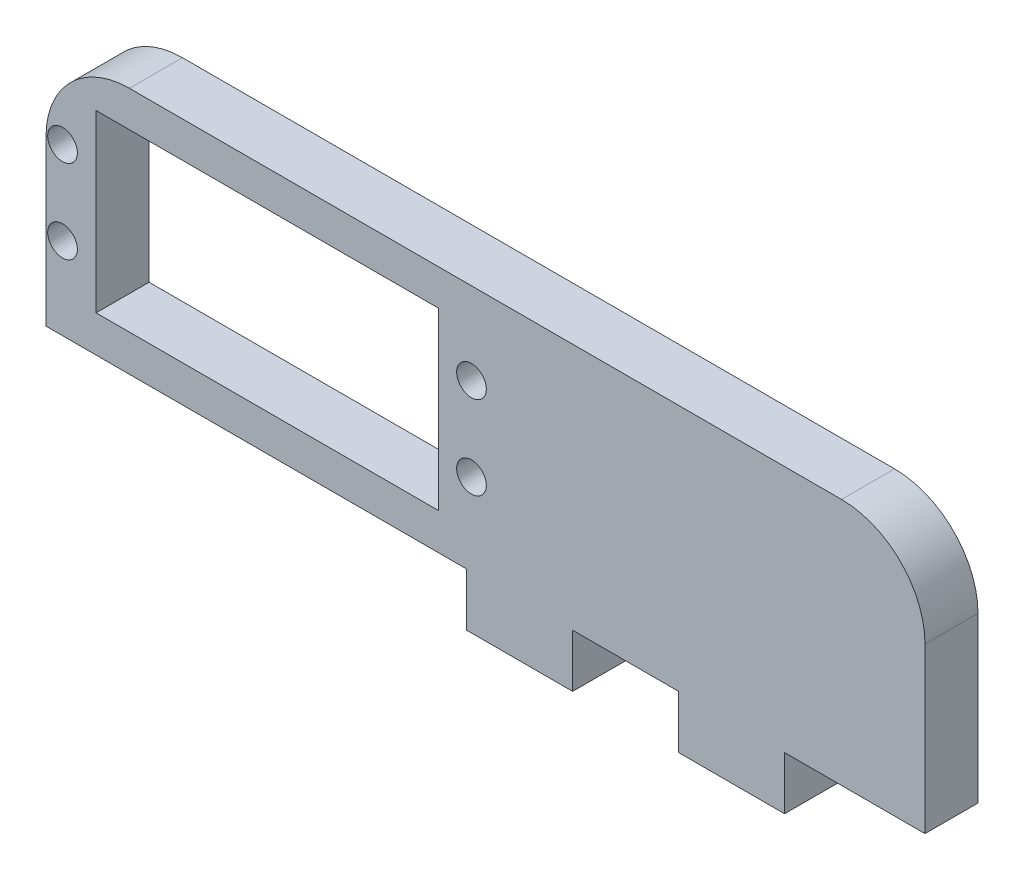
SolidWorks part; units mm, degrees
ref_plane "Front Plane" through (0, 0, 0) normal (0, 0, 1) x (1, 0, 0)
ref_plane "Top Plane" through (0, 0, 0) normal (0, 1, 0) x (1, 0, 0)
ref_plane "Right Plane" through (0, 0, 0) normal (1, 0, 0) x (0, 0, -1)
sketch "Sketch1" plane through (0, 0, 0) normal (0, 0, 1) x (1, 0, 0)
  line L0 (19.05, 38.1) -> (19.05, 44.45)
  line L1 (19.05, 44.45) -> (35.8724, 44.45)
  line L2 (38.1, 44.45) -> (-38.1, 44.45) construction
  line L3 (35.8724, 44.45) -> (35.8724, 74.1299)
  line L4 (35.8724, 74.1299) -> (-49.45, 74.1299)
  line L5 (19.05, 38.1) -> (6.35, 38.1)
  line L6 (6.35, 38.1) -> (6.35, 44.45)
  line L7 (6.35, 44.45) -> (-6.35, 44.45)
  line L8 (-6.35, 44.45) -> (-6.35, 38.1)
  line L9 (-6.35, 38.1) -> (-19.05, 38.1)
  line L10 (-19.05, 38.1) -> (-19.05, 44.45)
  line L11 (-19.05, 44.45) -> (-44.45, 44.45)
  line L12 (-44.45, 44.45) -> (-69.45, 44.45)
  line L13 (-69.45, 44.45) -> (-69.45, 74.1299)
  line L14 (-69.45, 74.1299) -> (-49.45, 74.1299)
  dimension "D1" = 20
  dimension "D2" = 25
extrude "Boss-Extrude1" add sketch "Sketch1" along normal blind 6.35
sketch "Sketch2" plane through (0, 0, 0) normal (0, 0, -1) x (-1, 0, 0)
  line L12 (-19.05, 38.1) -> (-6.35, 38.1)
  line L13 (-6.35, 38.1) -> (-6.35, 44.45)
  line L14 (-6.35, 44.45) -> (6.35, 44.45)
  line L15 (6.35, 44.45) -> (6.35, 38.1)
  line L16 (6.35, 38.1) -> (19.05, 38.1)
  line L17 (19.05, 38.1) -> (19.05, 44.45)
  line L18 (19.05, 44.45) -> (69.45, 44.45)
  line L19 (69.45, 44.45) -> (69.45, 74.1299)
  line L20 (69.45, 74.1299) -> (-35.8724, 74.1299)
  line L21 (-35.8724, 74.1299) -> (-35.8724, 44.45)
  line L22 (-35.8724, 44.45) -> (-19.05, 44.45)
  line L23 (-19.05, 44.45) -> (-19.05, 38.1)
  line L24 (-19.05, 38.1) -> (-6.35, 38.1)
  line L25 (-6.35, 38.1) -> (-6.35, 44.45)
  line L26 (-6.35, 44.45) -> (6.35, 44.45)
  line L27 (6.35, 44.45) -> (6.35, 38.1)
  line L28 (6.35, 38.1) -> (19.05, 38.1)
  line L29 (19.05, 38.1) -> (19.05, 44.45)
  line L30 (19.05, 44.45) -> (69.45, 44.45)
  line L31 (69.45, 44.45) -> (69.45, 74.1299)
  line L32 (69.45, 74.1299) -> (-35.8724, 74.1299)
  line L33 (-35.8724, 74.1299) -> (-35.8724, 44.45)
  line L34 (-35.8724, 44.45) -> (-19.05, 44.45)
  line L35 (-19.05, 44.45) -> (-19.05, 38.1)
  dimension "D1" = 0
sketch "Sketch3" plane through (0, 0, 6.35) normal (0, 0, 1) x (1, 0, 0)
  line L0 (-69.45, 44.45) -> (-69.45, 74.1299) construction
  line L1 (-63.45, 69.8299) -> (-22.45, 69.8299)
  line L2 (-63.45, 69.8299) -> (-63.45, 48.8299)
  line L3 (-63.45, 48.8299) -> (-22.45, 48.8299)
  line L4 (-22.45, 69.8299) -> (-22.45, 48.8299)
  line L5 (-69.45, 74.1299) -> (35.8724, 74.1299) construction
  circle A0 centre (-67.4705, 64.2899) radius 1.778
  circle A1 centre (-67.4705, 54.2899) radius 1.778
  circle A2 centre (-18.4705, 54.2899) radius 1.778
  circle A3 centre (-18.4705, 64.2899) radius 1.778
  dimension "D5" = 3.556
  dimension "D1" = 21
  dimension "D2" = 41
  dimension "D3" = 6
  dimension "D4" = 4.3
extrude "Cut-Extrude1" cut sketch "Sketch3" against normal through all
fillet "Fillet1" radius 10 2 edges at (-69.45, 74.1299, 3.175) (35.8724, 74.1299, 3.175)
